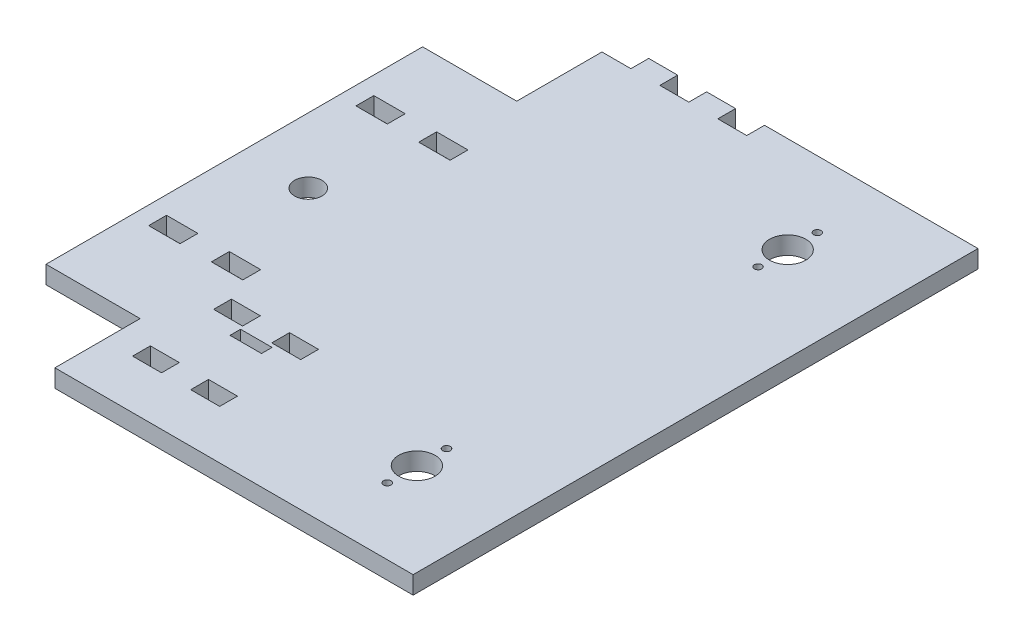
SolidWorks part; units mm, degrees
ref_plane "Front Plane" through (0, 0, 0) normal (0, 0, 1) x (1, 0, 0)
ref_plane "Top Plane" through (0, 0, 0) normal (0, 1, 0) x (1, 0, 0)
ref_plane "Right Plane" through (0, 0, 0) normal (1, 0, 0) x (0, 0, -1)
sketch "Sketch1" plane through (0, 0, 0) normal (0, 1, 0) x (1, 0, 0)
  line L1 (0, 0) -> (96.6555, 0)
  line L2 (0, 0) -> (0, 152.4)
  line L3 (0, 152.4) -> (96.6555, 152.4)
  line L4 (96.6555, 0) -> (96.6555, 152.4)
  line L5 (0, 0) -> (96.6555, 152.4) construction
  line L6 (0, 152.4) -> (96.6555, 0) construction
  point P4 (48.3277, 76.2)
  dimension "D1" = 96.6555
  dimension "D2" = 152.4
extrude "Boss-Extrude1" add sketch "Sketch1" along normal blind 4.8
ref_plane "Plane1" through (0, 0, -76.2) normal (0, 0, -1) x (-1, 0, 0)
sketch "Sketch3" plane through (0, 0, 0) normal (0, -1, 0) x (1, 0, 0)
  line L28 (7.8117, -152.4) -> (7.8117, -147.6)
  line L29 (7.8117, -147.6) -> (0, -147.6)
  line L30 (0, -147.6) -> (0, -152.4)
  line L31 (0, -152.4) -> (7.8117, -152.4)
  line L32 (23.4352, -147.6) -> (15.6234, -147.6)
  line L33 (15.6234, -147.6) -> (15.6234, -152.4)
  line L34 (15.6234, -152.4) -> (23.4352, -152.4)
  line L35 (23.4352, -152.4) -> (23.4352, -147.6)
  line L36 (39.0586, -147.6) -> (31.2469, -147.6)
  line L37 (31.2469, -147.6) -> (31.2469, -152.4)
  line L38 (31.2469, -152.4) -> (39.0586, -152.4)
  line L39 (39.0586, -152.4) -> (39.0586, -147.6)
  line L40 (31.2469, -39.8737) -> (31.2469, -35.0737)
  line L41 (31.2469, -35.0737) -> (23.4352, -35.0737)
  line L42 (23.4352, -35.0737) -> (23.4352, -39.8737)
  line L43 (23.4352, -39.8737) -> (31.2469, -39.8737)
  line L44 (15.5612, -39.8737) -> (15.5612, -35.0737)
  line L45 (15.5612, -35.0737) -> (7.7494, -35.0737)
  line L46 (7.7494, -35.0737) -> (7.7494, -39.8737)
  line L47 (7.7494, -39.8737) -> (15.5612, -39.8737)
  line L48 (15.5612, -18.008) -> (15.5612, -13.208)
  line L49 (15.5612, -13.208) -> (7.7494, -13.208)
  line L50 (7.7494, -13.208) -> (7.7494, -18.008)
  line L51 (7.7494, -18.008) -> (15.5612, -18.008)
  line L52 (31.2469, -18.008) -> (31.2469, -13.208)
  line L53 (31.2469, -13.208) -> (23.4352, -13.208)
  line L54 (23.4352, -13.208) -> (23.4352, -18.008)
  line L55 (23.4352, -18.008) -> (31.2469, -18.008)
extrude "Cut-Extrude2" cut sketch "Sketch3" against normal through all
sketch "Sketch5" plane through (0, 0, 0) normal (0, -1, 0) x (-1, 0, 0)
  line L1 (-16.0386, 34.0628) -> (-24.5386, 34.0628)
  line L2 (-16.0386, 34.0628) -> (-16.0386, 31.2105)
  line L3 (-16.0386, 31.2105) -> (-24.5386, 31.2105)
  line L4 (-24.5386, 34.0628) -> (-24.5386, 31.2105)
  line L5 (-16.0386, 34.0628) -> (-24.5386, 31.2105) construction
  line L6 (-16.0386, 31.2105) -> (-24.5386, 34.0628) construction
  point P4 (-20.2886, 32.6367)
  dimension "D1" = 8.5
extrude "Cut-Extrude3" cut sketch "Sketch5" against normal through all
sketch "Sketch6" plane through (0, 0, 0) normal (-1, 0, 0) x (0, 0, 1)
  line L0 (-147.6, 4.8) -> (0, 4.8) construction
  line L1 (-124.6, 4.8) -> (-23, 4.8)
  line L2 (-124.6, 4.8) -> (-124.6, 0)
  line L3 (-124.6, 0) -> (-23, 0)
  line L4 (-23, 4.8) -> (-23, 0)
  line L5 (-124.6, 4.8) -> (-23, 0) construction
  line L6 (-124.6, 0) -> (-23, 4.8) construction
  line L7 (-147.6, 0) -> (0, 0) construction
  line L8 (-124.6, 2.4) -> (-147.6, 2.4) construction
  line L9 (-147.6, 4.8) -> (-147.6, 0) construction
  line L10 (-23, 2.4) -> (0, 2.4) construction
  line L11 (0, 4.8) -> (0, 0) construction
  point P4 (-73.8, 2.4)
  dimension "D1" = 101.6
extrude "Boss-Extrude2" add sketch "Sketch6" along normal blind 25.4
sketch "Sketch7" plane through (0, 4.8, 0) normal (0, 1, 0) x (1, 0, 0)
  line L20 (96.6555, 152.4) -> (39.0586, 152.4)
  line L21 (39.0586, 152.4) -> (39.0586, 147.6)
  line L22 (39.0586, 147.6) -> (31.2469, 147.6)
  line L23 (31.2469, 147.6) -> (31.2469, 152.4)
  line L24 (31.2469, 152.4) -> (23.4352, 152.4)
  line L25 (23.4352, 152.4) -> (23.4352, 147.6)
  line L26 (23.4352, 147.6) -> (15.6234, 147.6)
  line L27 (15.6234, 147.6) -> (15.6234, 152.4)
  line L28 (15.6234, 152.4) -> (7.8117, 152.4)
  line L29 (7.8117, 152.4) -> (7.8117, 147.6)
  line L30 (7.8117, 147.6) -> (0, 147.6)
  line L31 (0, 147.6) -> (0, 124.6)
  line L32 (0, 124.6) -> (-25.4, 124.6)
  line L33 (-25.4, 124.6) -> (-25.4, 23)
  line L34 (-25.4, 23) -> (0, 23)
  line L35 (0, 23) -> (0, 0)
  line L36 (0, 0) -> (96.6555, 0)
  line L37 (96.6555, 0) -> (96.6555, 152.4)
  line L38 (96.6555, 152.4) -> (39.0586, 152.4)
  line L39 (39.0586, 152.4) -> (39.0586, 147.6)
  line L40 (39.0586, 147.6) -> (31.2469, 147.6)
  line L41 (31.2469, 147.6) -> (31.2469, 152.4)
  line L42 (31.2469, 152.4) -> (23.4352, 152.4)
  line L43 (23.4352, 152.4) -> (23.4352, 147.6)
  line L44 (23.4352, 147.6) -> (15.6234, 147.6)
  line L45 (15.6234, 147.6) -> (15.6234, 152.4)
  line L46 (15.6234, 152.4) -> (7.8117, 152.4)
  line L47 (7.8117, 152.4) -> (7.8117, 147.6)
  line L48 (7.8117, 147.6) -> (0, 147.6)
  line L49 (0, 147.6) -> (0, 124.6)
  line L50 (0, 124.6) -> (-25.4, 124.6)
  line L51 (-25.4, 124.6) -> (-25.4, 23)
  line L52 (-25.4, 23) -> (0, 23)
  line L53 (0, 23) -> (0, 0)
  line L54 (0, 0) -> (96.6555, 0)
  line L55 (96.6555, 0) -> (96.6555, 152.4)
  circle A0 centre (-7.8004, 76.1615) radius 3.683
  dimension "D2" = 7.366
  dimension "D1" = 0
extrude "Cut-Extrude4" cut sketch "Sketch7" against normal through all contours A0
sketch "Sketch8" plane through (0, 4.8, 0) normal (0, 1, 0) x (1, 0, 0)
  line L16 (-20.58, 45.8718) -> (-12.1133, 45.8718)
  line L17 (-12.1133, 45.8718) -> (-12.1133, 50.6978)
  line L18 (-12.1133, 50.6978) -> (-20.58, 50.6978)
  line L19 (-20.58, 50.6978) -> (-20.58, 45.8718)
  line L20 (4.82, 50.6978) -> (-3.6466, 50.6978)
  line L21 (-3.6466, 50.6978) -> (-3.6466, 45.8718)
  line L22 (-3.6466, 45.8718) -> (4.82, 45.8718)
  line L23 (4.82, 45.8718) -> (4.82, 50.6978)
  line L24 (-20.58, 101.8042) -> (-12.1133, 101.8042)
  line L25 (-12.1133, 101.8042) -> (-12.1133, 106.6302)
  line L26 (-12.1133, 106.6302) -> (-20.58, 106.6302)
  line L27 (-20.58, 106.6302) -> (-20.58, 101.8042)
  line L28 (4.82, 106.6302) -> (-3.6466, 106.6302)
  line L29 (-3.6466, 106.6302) -> (-3.6466, 101.8042)
  line L30 (-3.6466, 101.8042) -> (4.82, 101.8042)
  line L31 (4.82, 101.8042) -> (4.82, 106.6302)
extrude "Cut-Extrude5" cut sketch "Sketch8" against normal through all
sketch "Sketch9" plane through (0, 4.8, 0) normal (0, 1, 0) x (1, 0, 0)
  line L2 (71.2555, 118.449) -> (71.2555, 134.449) construction
  line L3 (71.7132, 17.95) -> (71.7132, 33.95) construction
  circle A4 centre (71.2555, 118.449) radius 1
  circle A5 centre (71.2555, 134.449) radius 1
  circle A6 centre (71.2555, 126.449) radius 8 construction
  circle A7 centre (71.7132, 25.95) radius 8 construction
  circle A9 centre (71.7132, 33.95) radius 1.016
  circle A10 centre (71.7132, 17.95) radius 1.016
  circle A11 centre (71.7132, 25.95) radius 4.9 construction
  circle A12 centre (71.2555, 126.449) radius 4.9 construction
  circle A13 centre (71.7132, 25.95) radius 4.9
  circle A14 centre (71.2555, 126.449) radius 4.9
  point P0 (71.2555, 134.449)
  dimension "D1" = 2
  dimension "D2" = 2.032
extrude "Cut-Extrude6" cut sketch "Sketch9" against normal through all
equation "\"MDF\"= 4.8mm"
equation "\"Foamcore\"= 4.6mm"
equation "\"PCB\" = 1.6mm"
equation "\"GMaterial\"= \"MDF\""
equation "\"BaseWidth\" = 10in"
equation "\"SkidLength\" = 1in"
equation "\"SkidClearance\" = 0.4in"
equation "\"MotorMountLength\" = 2in"
equation "\"MotorMountWidth\" = \"GMaterial\""
equation "\"MotorMountHeight\" = 2.25in"
equation "\"UnoStackWidth\" = 77.4mm"
equation "\"UnoStackLength\" = 79.8mm"
equation "\"UnoStackHeight\" = 34.2mm"
equation "\"TallHexRiserHeight\" = 22.2mm"
equation "\"PingPongBallSize\" = 40mm"
equation "\"BarrelLength\" = 9in"
equation "\"BarrelSize\" = \"PingPongBallSize\""
equation "\"PlatformLength\" = 4in"
equation "\"PlatformWidth\" = 6in"
equation "\"D1@Sketch1\"=\"MDF\"+\"PivotHoleRadius\"+3"
equation "\"D2@Sketch1\"=\"PlatformWidth\""
equation "\"D1@Boss-Extrude1\"=\"MDF\""
equation "\"WheelDiameter\"=2.99213"
equation "\"ServoMountLength\"= 1.53774"
equation "\"ServoMountHeight\"=2.49223"
equation "\"ServoGearHeight\" = 0.95330261in"
equation "\"PivotHoleRadius\"= 0.616358"
equation "\"PlatformMountHeight\" = 3.19"
equation "\"TensionOffSet\"= .3mm"
equation "\"MotorMountWedge\"=0.333333"
equation "\"LaserCutterOffset\"= .3mm"
equation "\"D1@Boss-Extrude1\"=\"GMaterial\""
equation "\"BumperWidth\"=11"
equation "\"PitcherWheelCompression\" = 2.5mm"
equation "\"PitchingWheelWidth\" = 26.2mm"
equation "\"PitchingWheelDiameter\" = 65.5mm"
equation "\"PitchingWheelMountOffset\" = 8.4mm"
equation "\"PitchingWheelInnerDiameter\" = 45.5mm"
equation "\"PitchingWheelBoltShoulder\" = 4.5mm"
equation "\"BrassCouplingLength\" = 18mm"
equation "\"PitchingMotorHeight\" = 57.0mm"
equation "\"PitchingMotorShaftTopHeight\" = \"PitchingMotorHeight\" - 44.1mm"
equation "\"PitchingMotorBodyHeight\" = 38mm"
equation "\"PitchingMotorTopShoulderHeight\" = 40.6mm - \"PitchingMotorBodyHeight\" "
equation "\"PitchingMotorBottomShoulderHeight\" = 40.2mm - \"PitchingMotorBodyHeight\""
equation "\"PitchingMotorBottomShaftHeight\" = \"PitchingMotorHeight\" - \"PitchingMotorShaftTopHeight\" - \"PitchingMotorTopShoulderHeight\" - \"PitchingMotorBodyHeight\" - \"PitchingMotorBottomShoulderHeight\""
equation "\"PitchingMotorShaftDiameter\" = 2.2mm"
equation "\"PitchingMotorBodyDiameter\" = 27.4mm"
equation "\"PitchingMotorTopShoulderDiameter\" = 9.8mm"
equation "\"PitchingMotorBottomShoulderDiameter\" = 9.8mm"
equation "\"BrassCouplingHexSize\" = 12mm"
equation "\"BrassCouplingBoreSize\" = 3.17mm"
equation "\"PitchingMotorMountingHoleDistance\" = 16mm"
equation "\"Acrylic\" = 4.4mm"
equation "\"PitchingMotorDistance\" = \"PitchingWheelDiameter\" + \"PingPongBallSize\" - \"PitcherWheelCompression\"*2"
equation "\"DCMotorMountingScrewDiameter\"=0.0787402"
equation "\"D1@Sketch9\"=\"DCMotorMountingScrewDiameter\""
